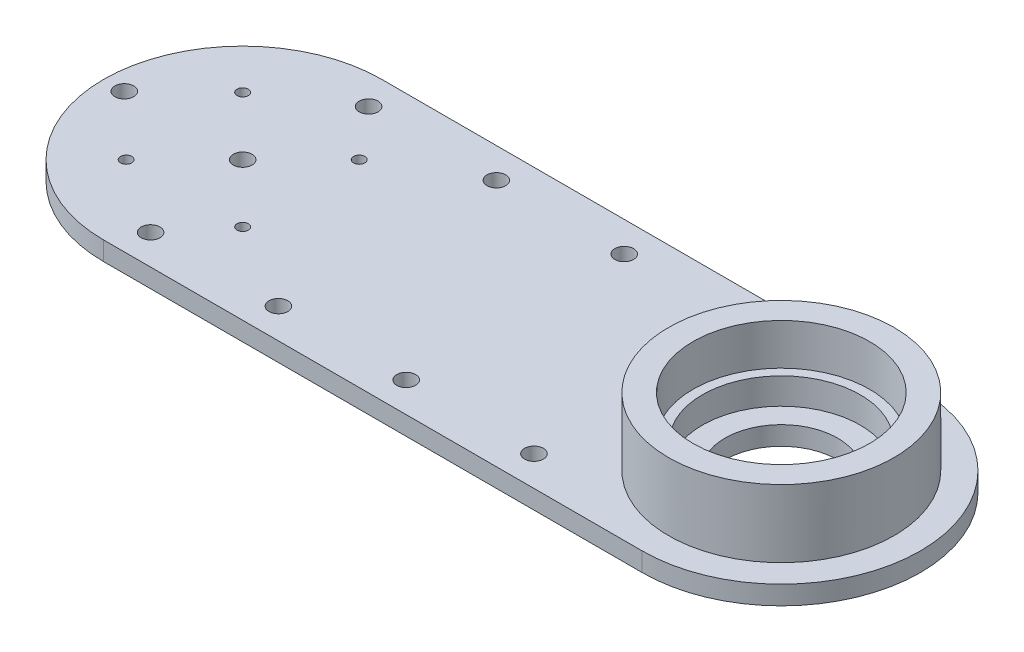
SolidWorks part; units mm, degrees
ref_plane "Front Plane" through (0, 0, 0) normal (0, 0, 1) x (1, 0, 0)
ref_plane "Top Plane" through (0, 0, 0) normal (0, 1, 0) x (1, 0, 0)
ref_plane "Right Plane" through (0, 0, 0) normal (1, 0, 0) x (0, 0, -1)
sketch "Sketch1" plane through (0, 0, 0) normal (0, 1, 0) x (1, 0, 0)
  line L0 (0, 37) -> (143.3, 37)
  line L2 (143.3, -37) -> (0, -37)
  arc A1 (0, -37) -> (0, 37) centre (0, 0) cw
  arc A2 (143.3, 37) -> (143.3, -37) centre (143.3, 0) cw
  dimension "D1" = 143.3
extrude "Boss-Extrude1" add sketch "Sketch1" along normal blind 5
sketch "Sketch2" plane through (0, 5, 0) normal (0, 1, 0) x (1, 0, 0)
  circle A0 centre (0, 0) radius 2.5
  circle A1 centre (-15.5, 15.5) radius 1.5
  circle A2 centre (15.5, 15.5) radius 1.5
  circle A3 centre (15.5, -15.5) radius 1.5
  circle A4 centre (-15.5, -15.5) radius 1.5
  circle A5 centre (143.3, 0) radius 15
  dimension "D2" = 30
  dimension "D1" = 143.3
extrude "Cut-Extrude1" cut sketch "Sketch2" against normal blind 5
sketch "Sketch3" plane through (0, 5, 0) normal (0, 1, 0) x (1, 0, 0)
  line L1 (0, 34) -> (143.3, 34)
  line L2 (0, -34) -> (143.3, -34)
  line L5 (9, 34) -> (34, 34)
  line L6 (9, -34) -> (34, -34)
  line L9 (43, 34) -> (68, 34)
  line L11 (43, -34) -> (68, -34)
  line L13 (77, 34) -> (102, 34)
  line L16 (77, -34) -> (102, -34)
  arc A1 (143.3, -34) -> (143.3, 34) centre (143.3, 0) ccw
  arc A2 (0, 34) -> (0, -34) centre (0, 0) ccw
  circle A3 centre (4.5, 29) radius 2.5
  circle A4 centre (38.5, 29) radius 2.5
  circle A5 centre (72.5, 29) radius 2.5
  circle A6 centre (106.5, 29) radius 2.5
  circle A7 centre (4.5, -29) radius 2.5
  circle A8 centre (38.5, -29) radius 2.5
  circle A9 centre (72.5, -29) radius 2.5
  circle A10 centre (106.5, -29) radius 2.5
  circle A11 centre (-31.5, 0) radius 2.5
  point P12 (0, 0)
extrude "Cut-Extrude2" cut sketch "Sketch3" against normal blind 5 contours A11 | A7 | A8 | A9 | A10 | A3 | A4 | A5 | A6
sketch "Sketch4" plane through (0, 5, 0) normal (0, 1, 0) x (1, 0, 0)
  circle A0 centre (143.3, 0) radius 21.001
  circle A1 centre (143.3, 0) radius 23.5
  dimension "D1" = 47
extrude "Boss-Extrude2" add sketch "Sketch4" along normal blind 7
sketch "Sketch5" plane through (0, 5, 0) normal (0, 1, 0) x (1, 0, 0)
  circle A0 centre (143.3, 0) radius 30.0007
  circle M1 centre (143.3, 0) radius 23.5
extrude "Boss-Extrude3" add sketch "Sketch5" along normal blind 18 contours A0 M1
